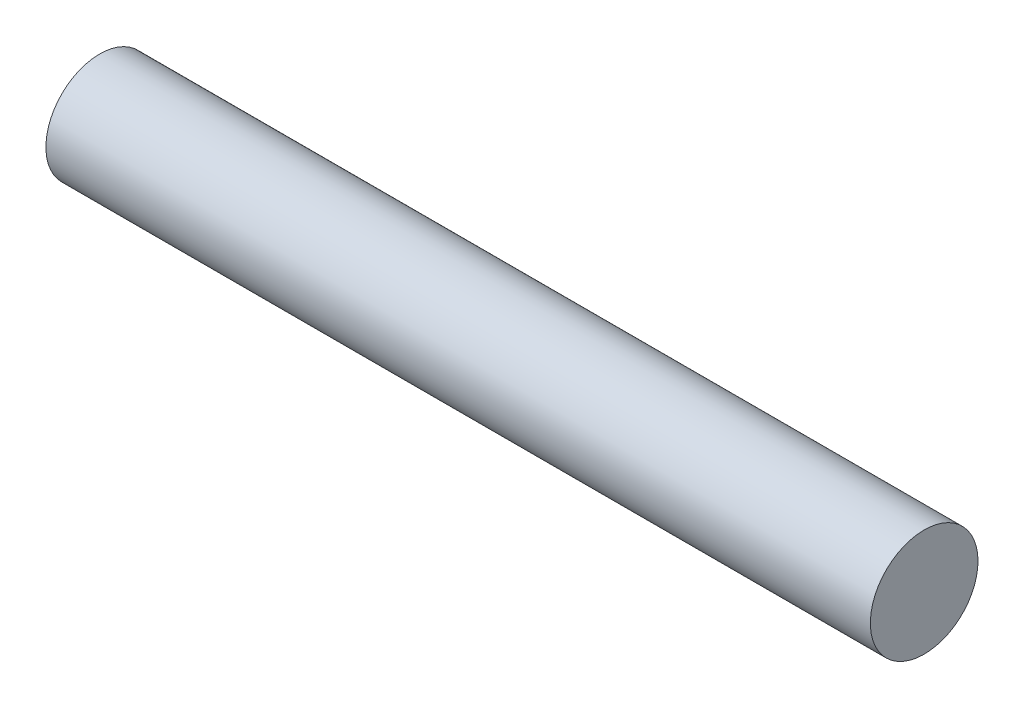
SolidWorks part; units mm, degrees
ref_plane "Front Plane" through (0, 0, 0) normal (0, 0, 1) x (1, 0, 0)
ref_plane "Top Plane" through (0, 0, 0) normal (0, 1, 0) x (1, 0, 0)
ref_plane "Right Plane" through (0, 0, 0) normal (1, 0, 0) x (0, 0, -1)
sketch "Sketch1" plane through (0, 0, 0) normal (1, 0, 0) x (0, 0, -1)
  circle A0 centre (0, 0) radius 49.022
  dimension "D1" = 98.044
extrude "Boss-Extrude1" add sketch "Sketch1" along normal blind 751
